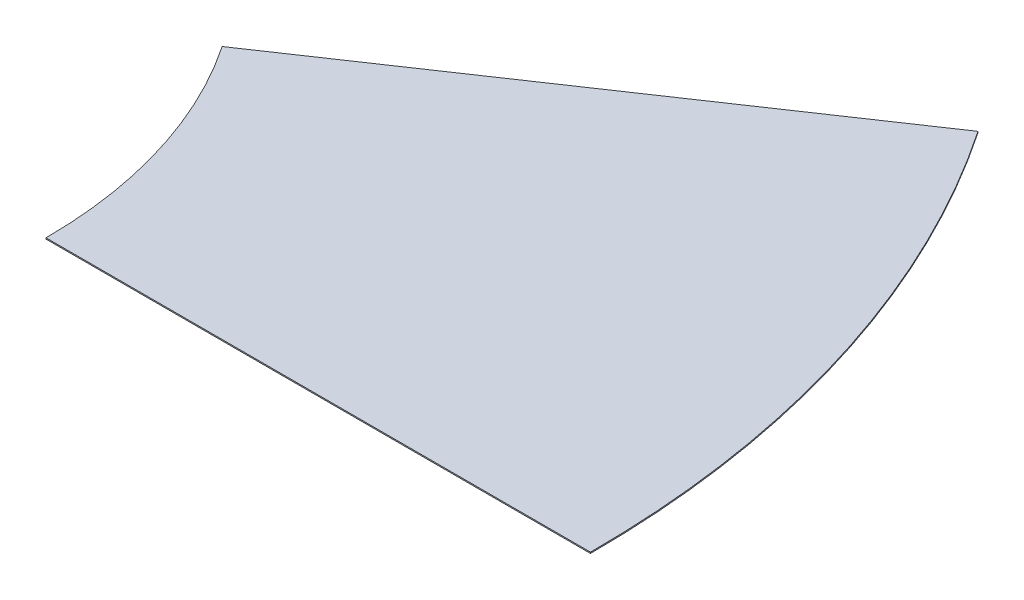
SolidWorks part; units mm, degrees
ref_plane "Front" through (0, 0, 0) normal (0, 0, 1) x (1, 0, 0)
ref_plane "Top" through (0, 0, 0) normal (0, 1, 0) x (1, 0, 0)
ref_plane "Right" through (0, 0, 0) normal (1, 0, 0) x (0, 0, -1)
sketch "草图1" plane through (0, 0, 0) normal (0, 1, 0) x (1, 0, 0)
  line L0 (0, 0) -> (110, 0) construction
  line L1 (91.1941, 61.5112) -> (0, 0) construction
  line L2 (91.1941, 61.5112) -> (41.4519, 27.9596)
  line L3 (110, 0) -> (50, 0)
  arc A0 (110, 0) -> (91.1941, 61.5112) centre (0, 0) ccw
  arc A1 (50, 0) -> (41.4519, 27.9596) centre (0, 0) ccw
  dimension "D2" = 50
  dimension "D3" = 110
  dimension "D1" = 34
extrude "凸台-拉伸1" add sketch "草图1" along normal blind 0.13 contours L3 A1 L2 A0
